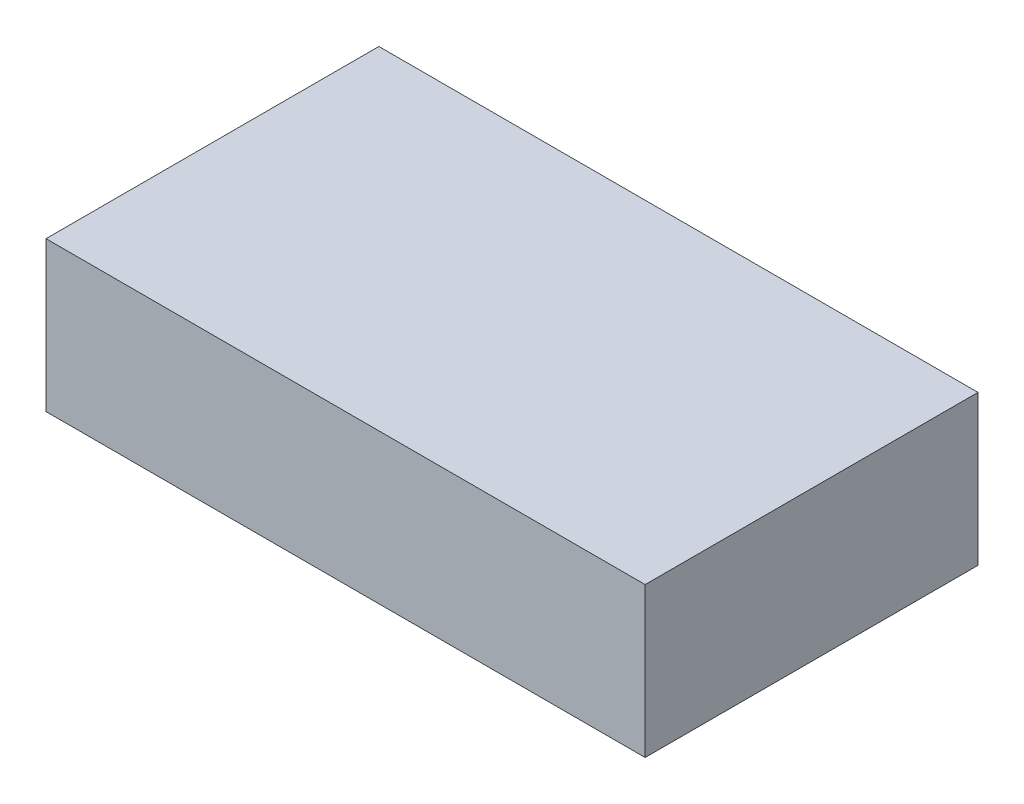
SolidWorks part; units mm, degrees
ref_plane "Front Plane" through (0, 0, 0) normal (0, 0, 1) x (1, 0, 0)
ref_plane "Top Plane" through (0, 0, 0) normal (0, 1, 0) x (1, 0, 0)
ref_plane "Right Plane" through (0, 0, 0) normal (1, 0, 0) x (0, 0, -1)
sketch "Sketch1" plane through (0, 0, 0) normal (0, 1, 0) x (1, 0, 0)
  line L1 (0, 0) -> (57.15, 0)
  line L2 (0, 0) -> (0, 31.75)
  line L3 (0, 31.75) -> (57.15, 31.75)
  line L4 (57.15, 0) -> (57.15, 31.75)
  dimension "D1" = 31.75
  dimension "D2" = 57.15
extrude "Boss-Extrude1" add sketch "Sketch1" along normal blind 14.2875
